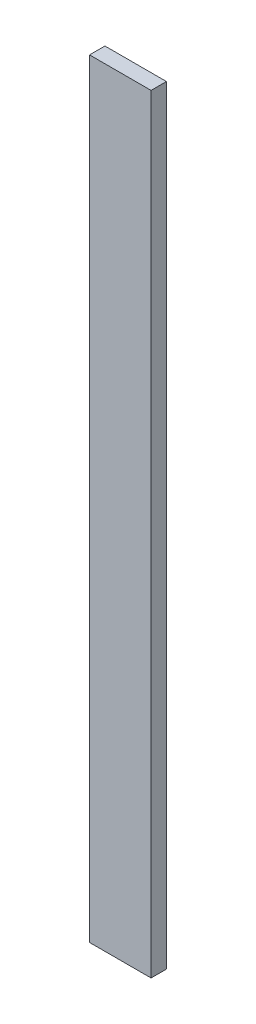
SolidWorks part; units mm, degrees
ref_plane "Front Plane" through (0, 0, 0) normal (0, 0, 1) x (1, 0, 0)
ref_plane "Top Plane" through (0, 0, 0) normal (0, 1, 0) x (1, 0, 0)
ref_plane "Right Plane" through (0, 0, 0) normal (1, 0, 0) x (0, 0, -1)
sketch "Sketch1" plane through (0, 0, 0) normal (0, 0, 1) x (1, 0, 0)
  line L1 (-12.7, 158.75) -> (12.7, 158.75)
  line L2 (-12.7, 158.75) -> (-12.7, -158.75)
  line L3 (-12.7, -158.75) -> (12.7, -158.75)
  line L4 (12.7, 158.75) -> (12.7, -158.75)
  line L5 (-12.7, 158.75) -> (12.7, -158.75) construction
  line L6 (-12.7, -158.75) -> (12.7, 158.75) construction
  point P0 (0, 0)
  dimension "D1" = 317.5
  dimension "D2" = 25.4
extrude "Boss-Extrude1" add sketch "Sketch1" along normal blind 6.35
